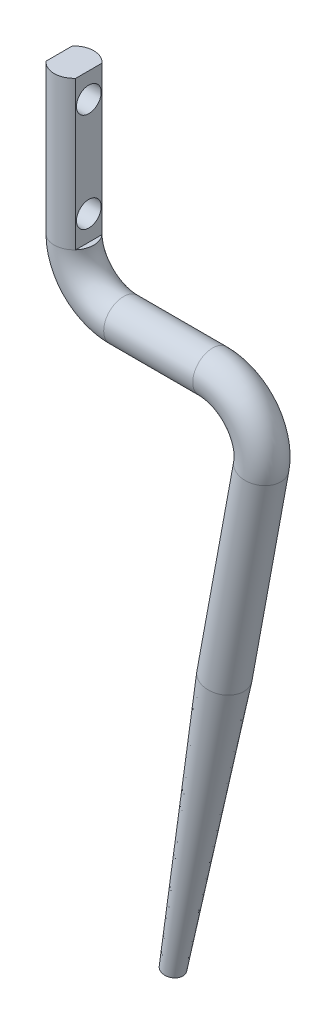
SolidWorks part; units mm, degrees
material "AISI 304"
ref_plane "前视基准面" through (0, 0, 0) normal (0, 0, 1) x (1, 0, 0)
ref_plane "上视基准面" through (0, 0, 0) normal (0, 1, 0) x (1, 0, 0)
ref_plane "右视基准面" through (0, 0, 0) normal (1, 0, 0) x (0, 0, -1)
sketch "Sketch1" plane through (0, 0, 0) normal (0, 0, 1) x (1, 0, 0)
  line L0 (0, 40) -> (0, 10)
  line L1 (10, 0) -> (27.9882, 0)
  line L2 (37.8225, -11.8128) -> (20, -108.5)
  arc A0 (27.9882, 0) -> (37.8225, -11.8128) centre (27.9882, -10) cw
  arc A1 (0, 10) -> (10, 0) centre (10, 10) ccw
  point P7 (40, 0)
  point P10 (0, 0)
  dimension "D5" = 10
  dimension "D1" = 40
  dimension "D2" = 40
  dimension "D3" = 108.5
  dimension "D4" = 20
ref_plane "Plane1" through (0, 40, 0) normal (0, 1, 0) x (1, 0, 0)
sketch "Sketch3" plane through (0, 40, 0) normal (0, 1, 0) x (1, 0, 0)
  circle A0 centre (0, 0) radius 4
  dimension "D1" = 8
sweep "Sweep1" add profiles "Sketch3" path "Sketch1"
chamfer "Chamfer1" distance 2 angle 88 1 edges at (20, -108.5, 4)
sketch "Sketch4" plane through (0, 40, 0) normal (0, 1, 0) x (1, 0, 0)
  line L1 (3, 17.7651) -> (-3, 17.7651)
  line L2 (3, 17.7651) -> (3, -17.7651)
  line L3 (3, -17.7651) -> (-3, -17.7651)
  line L4 (-3, 17.7651) -> (-3, -17.7651)
  line L5 (3, 17.7651) -> (-3, -17.7651) construction
  line L6 (3, -17.7651) -> (-3, 17.7651) construction
  point P0 (0, 0)
  dimension "D1" = 3
extrude "Extrude1" cut sketch "Sketch4" against normal blind 30 flip side to cut
hole_wizard "M6 Tapped Hole1" positions "Sketch5" profile "Sketch6" tap size "M6" standard "GB"
sketch "Sketch5" plane through (3, 0, 0) normal (1, 0, 0) x (0, 0, -1)
  line L0 (-2.6458, 10) -> (2.6458, 10) construction
  point P0 (0, 35)
  point P2 (0, 15)
  dimension "D1" = 20
  dimension "D2" = 5
sketch "Sketch6" plane through (3, 35, 0) normal (0, 1, 0) x (0, 0, -1)
  line L0 (0, 0) -> (0, 10.5022)
  line L1 (0, 10.5022) -> (2.5, 9)
  line L2 (2.5, 9) -> (2.5, 0)
  line L5 (2.5, 0) -> (0, 0)
  line L10 (0, 10.5022) -> (-2.5, 9) construction
  line L11 (0, -6.35) -> (0, 107.95) construction
  dimension "螺纹孔钻头直径" = 5
  dimension "螺纹孔钻头深度" = 9
  dimension "导头角度" = 118
